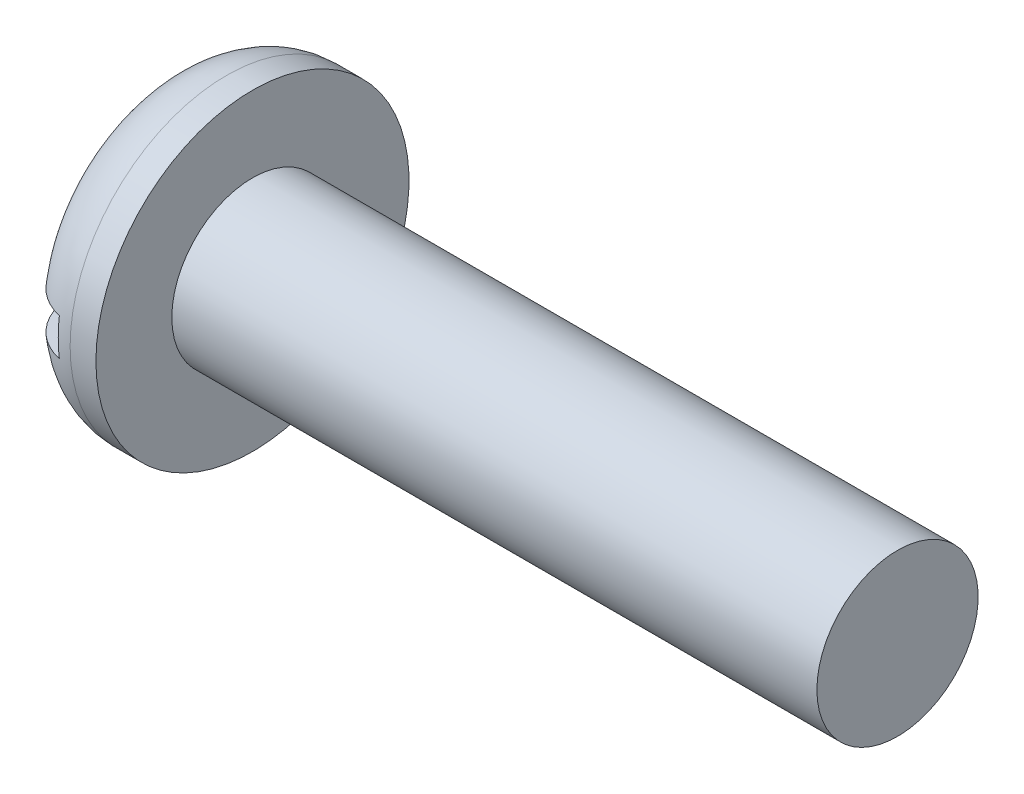
SolidWorks part; units mm, degrees
ref_plane "Plane1" through (0, 0, 0) normal (0, 0, 1) x (1, 0, 0)
ref_plane "Plane2" through (0, 0, 0) normal (0, 1, 0) x (1, 0, 0)
ref_plane "Plane3" through (0, 0, 0) normal (1, 0, 0) x (0, 0, -1)
sketch "BodySke" plane through (0, 0, 0) normal (0, 0, 1) x (1, 0, 0)
  line L0 (5.1562, 4.7625) -> (5.1562, 9.2456)
  line L1 (0, 0) -> (0, 5.6134)
  line L2 (-25.4, 0) -> (127, 0) construction
  line L3 (43.2562, 0) -> (0, 0)
  line L4 (5.1562, 4.7625) -> (43.2562, 4.7625)
  line L5 (43.2562, 4.7625) -> (43.2562, 0)
  line L6 (3.6322, 9.2456) -> (5.1562, 9.2456)
  line L7 (5.1562, -4.7625) -> (43.2562, -4.7625) construction
  line L8 (0, -9.2456) -> (5.1562, -9.2456) construction
  line L9 (6.7437, 6.35) -> (6.7437, -3.175) construction
  line L10 (11.5062, 6.35) -> (11.5062, -3.175) construction
  arc A0 (0, 5.6134) -> (3.6322, 9.2456) centre (3.6322, 5.6134) cw
  point P15 (0, 9.2456)
  dimension "Head_fillet_rad" = 3.6322
  dimension "Diameter" = 9.525
  dimension "Length" = 38.1
  dimension "Head_ht" = 5.1562
  dimension "Head_dia" = 18.4912
  dimension "Advance" = 1.5875
  dimension "Thread_nom" = 31.75
revolve "Base-Revolve" add sketch "BodySke" angle 360 about L2
cosmetic thread "ThreadCosmetic" [suppressed] parameters "Thread_length"=31.75, "Thread_minor"=7.9375
sketch "Sketch2" plane through (0, 0, 0) normal (1, 0, 0) x (0, 0, -1)
  line L0 (9.2456, -1.1049) -> (-9.2456, -1.1049)
  line L1 (9.2456, -1.1049) -> (9.2456, 1.1049)
  line L2 (-9.2456, 1.1049) -> (9.2456, 1.1049)
  line L3 (-9.2456, 1.1049) -> (-9.2456, -1.1049)
  dimension "D1" = 18.4912
  dimension "Slot_width" = 2.2098
  dimension "D2" = 9.2456
  dimension "D3" = 1.1049
extrude "Slot" cut sketch "Sketch2" along normal blind 2.8448
sketch "ThdSchSke" plane through (0, 0, 0) normal (0, 0, 1) x (1, 0, 0)
  line L0 (11.5062, -3.9688) -> (10.9504, -4.7625)
  line L1 (11.5062, -3.9688) -> (12.062, -4.7625)
  line L2 (12.062, -4.7625) -> (12.062, -5.9531)
  line L3 (-3.175, 0) -> (5.1513, 0) construction
  line L5 (12.062, -5.9531) -> (10.9504, -5.9531)
  line L6 (10.9504, -5.9531) -> (10.9504, -4.7625)
  dimension "Diameter" = 9.525
  dimension "SideAngle" = 55
  dimension "VeeAngle" = 70
  dimension "Thread_minor" = 7.9375
  dimension "Overcut" = 11.9063
  dimension "Start" = 11.5062
revolve "ThreadSchematic" [suppressed] cut sketch "ThdSchSke" angle 360 about L3
pattern_linear "ThdSchPat" [suppressed]
equation "\"D1@Sketch2\" = \"Head_dia@BodySke\""
equation "\"D2@Sketch2\" = \"D1@Sketch2\" / 2"
equation "\"D3@Sketch2\" = \"Slot_width@Sketch2\" / 2"
equation "\"Thread_length@ThreadCosmetic\" = ((sgn( (\"Length@BodySke\" - \"Advance@BodySke\" ) - \"Thread_nom@BodySke\" )-1)*( (\"Length@BodySke\" - \"Advance@BodySke\" ) - \"Thread_nom@BodySke\" ))/-2+ \"Thread_nom@BodySke\""
equation "\"Thread_minor@ThdSchSke\" = \"Thread_minor@ThreadCosmetic\""
equation "\"Diameter@ThdSchSke\" = \"Diameter@BodySke\""
equation "\"Overcut@ThdSchSke\" = \"Diameter@BodySke\" * 1.25"
equation "\"Start@ThdSchSke\" = \"Head_ht@BodySke\" + \"Length@BodySke\" - \"Thread_length@ThreadCosmetic\"  '---Non-countersunk---"
equation "\"Num_threads@ThdSchPat\" = int( \"Thread_length@ThreadCosmetic\" / \"Advance@BodySke\" + 0.999 )  + 1"
equation "\"Advance@ThdSchPat\" = \"Thread_length@ThreadCosmetic\" /  (\"Num_threads@ThdSchPat\" - 1) 'relax it"
